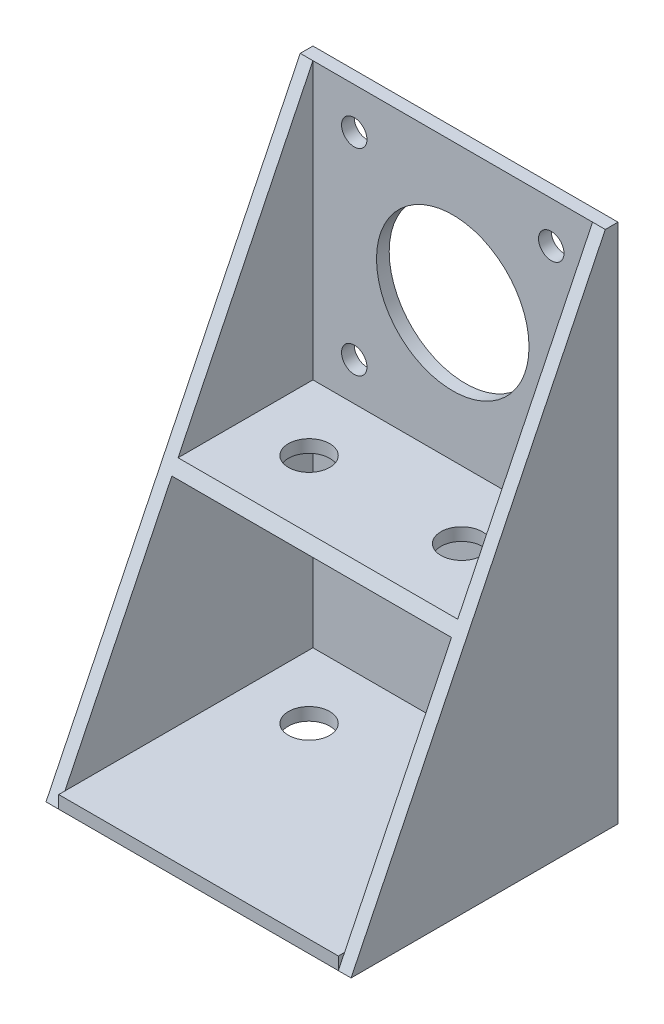
SolidWorks part; units mm, degrees
ref_plane "Alzado" through (0, 0, 0) normal (0, 0, 1) x (1, 0, 0)
ref_plane "Planta" through (0, 0, 0) normal (0, 1, 0) x (1, 0, 0)
ref_plane "Vista lateral" through (0, 0, 0) normal (1, 0, 0) x (0, 0, -1)
sketch "Croquis1" plane through (0, 0, 0) normal (0, 0, 1) x (1, 0, 0)
  line L1 (-22, 22) -> (22, 22)
  line L2 (-22, 22) -> (-22, -22)
  line L3 (-22, -22) -> (22, -22)
  line L4 (22, 22) -> (22, -22)
  line L5 (-22, 22) -> (22, -22) construction
  line L6 (-22, -22) -> (22, 22) construction
  point P0 (0, 0)
  dimension "D1" = 44
extrude "Saliente-Extruir1" add sketch "Croquis1" along normal blind 2
sketch "Croquis2" plane through (0, 0, 2) normal (0, 0, 1) x (1, 0, 0)
  line L0 (-22, 22) -> (22, -22) construction
  line L2 (-15.5, 15.5) -> (15.5, 15.5)
  line L3 (-15.5, 15.5) -> (-15.5, -15.5)
  line L4 (-15.5, -15.5) -> (15.5, -15.5)
  line L5 (15.5, 15.5) -> (15.5, -15.5)
  line L6 (-15.5, 15.5) -> (15.5, -15.5) construction
  line L7 (-15.5, -15.5) -> (15.5, 15.5) construction
  circle A0 centre (0, 0) radius 12
  circle A1 centre (-15.5, 15.5) radius 2
  circle A2 centre (15.5, 15.5) radius 2
  circle A3 centre (15.5, -15.5) radius 2
  circle A4 centre (-15.5, -15.5) radius 2
  dimension "D1" = 24
  dimension "D4" = 4
  dimension "D2" = 31
  dimension "D3" = 31
extrude "Cortar-Extruir1" cut sketch "Croquis2" against normal blind 2 contours A1 | A0 | A2 | A4 | A3
sketch "Croquis3" plane through (0, 0, 2) normal (0, 0, 1) x (1, 0, 0)
  line L0 (0, 0) -> (0, -60) construction
  line L1 (22, -22) -> (22, -60) construction
  line L2 (22, -60) -> (0, -60) construction
  line L4 (-22, -22) -> (22, -22)
  line L5 (-22, -22) -> (-22, -60)
  line L6 (-22, -60) -> (22, -60)
  line L7 (22, -22) -> (22, -60)
  dimension "D1" = 60
extrude "Saliente-Extruir2" add sketch "Croquis3" against normal blind 2
sketch "Croquis4" plane through (0, 0, 2) normal (0, 0, 1) x (1, 0, 0)
  line L3 (-22, -21.5) -> (22, -21.5)
  line L8 (-22, -21.5) -> (-22, -23.5)
  line L9 (-22, -23.5) -> (22, -23.5)
  line L10 (22, -21.5) -> (22, -23.5)
  line L11 (0, -21.5) -> (22, -23.5) construction
  line L12 (-22, -23.5) -> (0, -21.5) construction
  point P0 (0, 0)
  point P6 (0, -21.5)
  dimension "D4" = 44
extrude "Saliente-Extruir3" add sketch "Croquis4" along normal blind 29
sketch "Croquis5" plane through (-22, 0, 0) normal (-1, 0, 0) x (0, 0, 1)
  line L0 (2, 22) -> (42, -60)
  line L2 (42, -60) -> (2, -60)
  line L3 (2, 22) -> (2, -21.5) construction
  line L4 (2, 22) -> (0, 22) construction
  line L5 (2, -60) -> (0, -60)
  line L6 (0, -60) -> (0, 22)
  line L7 (0, 22) -> (2, 22)
  dimension "D1" = 40
extrude "Saliente-Extruir4" add sketch "Croquis5" along normal blind 2
sketch "Croquis7" plane through (22, 0, 0) normal (1, 0, 0) x (0, 0, -1)
  line L0 (0, -60) -> (-42, -60)
  line L1 (-42, -60) -> (-2, 22)
  line L2 (-2, 22) -> (0, 22)
  line L3 (0, 22) -> (0, -60)
extrude "Saliente-Extruir5" add sketch "Croquis7" along normal blind 2
sketch "Croquis8" plane through (22, 0, 0) normal (1, 0, 0) x (0, 0, -1)
  line L4 (-24.1951, -23.5) -> (-23.2195, -21.5)
  line L5 (-23.2195, -21.5) -> (-31, -21.5)
  line L6 (-31, -21.5) -> (-31, -23.5)
  line L7 (-31, -23.5) -> (-24.1951, -23.5)
  line L8 (-24.1951, -23.5) -> (-23.2195, -21.5)
  line L9 (-23.2195, -21.5) -> (-31, -21.5)
  line L10 (-31, -21.5) -> (-31, -23.5)
  line L11 (-31, -23.5) -> (-24.1951, -23.5)
  dimension "D1" = 0
extrude "Cortar-Extruir2" cut sketch "Croquis8" against normal up to surface (44 mm away) up to face at (-22, -22.5, 29.1768)
sketch "Croquis10" plane through (0, -60, 0) normal (0, -1, 0) x (1, 0, 0)
  line L1 (-22, 2) -> (22, 2)
  line L2 (-22, 2) -> (-22, 42)
  line L3 (-22, 42) -> (22, 42)
  line L4 (22, 2) -> (22, 42)
extrude "Saliente-Extruir6" add sketch "Croquis10" against normal blind 2
sketch "Croquis11" plane through (0, -21.5, 0) normal (0, 1, 0) x (1, 0, 0)
  line L0 (-22, -12.6098) -> (22, -12.6098) construction
  line L1 (-22, -23.2195) -> (-22, -2) construction
  line L2 (22, -2) -> (22, -23.2195) construction
  line L3 (0, -12.6098) -> (0, -18.2462) construction
  circle A0 centre (-12, -12.6098) radius 3.25
  circle A1 centre (12, -12.6098) radius 3.25
  dimension "D2" = 6.5
  dimension "D1" = 12
extrude "Cortar-Extruir3" cut sketch "Croquis11" against normal through all
